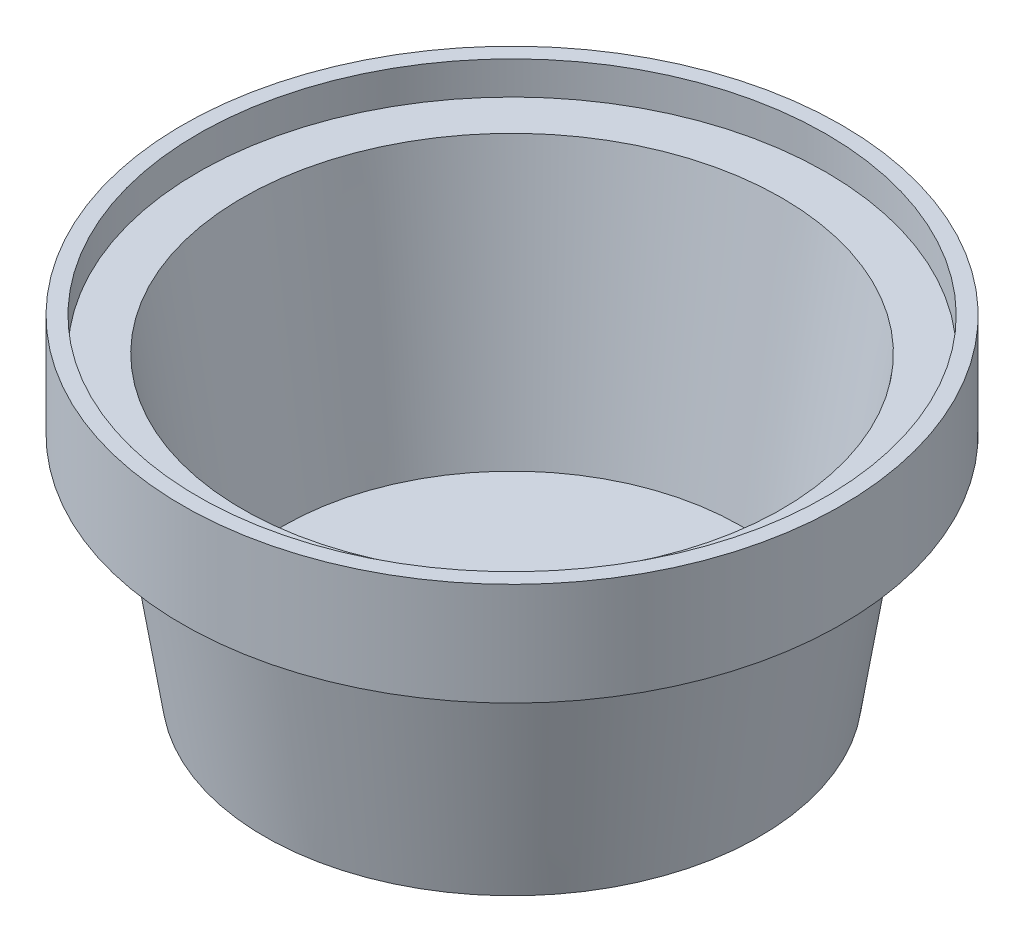
SolidWorks part; units mm, degrees
ref_plane "Front Plane" through (0, 0, 0) normal (0, 0, 1) x (1, 0, 0)
ref_plane "Top Plane" through (0, 0, 0) normal (0, 1, 0) x (1, 0, 0)
ref_plane "Right Plane" through (0, 0, 0) normal (1, 0, 0) x (0, 0, -1)
sketch "Sketch1" plane through (0, 0, 0) normal (0, 0, 1) x (1, 0, 0)
  line L0 (0, 0) -> (0, 40.9429) construction
  line L1 (37.465, 4.327) -> (44.1635, 47.507)
  line L2 (0, 4.327) -> (37.465, 4.327)
  line L3 (0, 4.327) -> (0, -0.753)
  line L4 (0, -0.753) -> (40.5325, -0.753)
  line L7 (47.625, 44.967) -> (40.5325, -0.753)
  line L9 (44.1635, 47.507) -> (51.435, 47.507)
  line L11 (47.625, 44.967) -> (51.435, 44.967)
  line L14 (53.975, 46.5741) -> (53.975, 36.077)
  line L15 (53.975, 36.077) -> (51.435, 36.077)
  line L16 (51.435, 44.967) -> (51.435, 36.077)
  line L18 (53.975, 46.5741) -> (53.975, 52.9241)
  line L19 (53.975, 52.9241) -> (51.435, 52.9241)
  line L20 (51.435, 47.507) -> (51.435, 52.9241)
  point P16 (34.4243, 47.507)
  point P17 (46.798, 49.1141)
  dimension "D1" = 5.08
  dimension "D2" = 3.81
  dimension "D3" = 2.54
  dimension "D4" = 2.54
  dimension "D5" = 6.35
  dimension "D6" = 43.18
  dimension "D7" = 8.89
  dimension "D8" = 37.465
  dimension "D9" = 3.81
  dimension "D10" = 47.625
revolve "Revolve1" add sketch "Sketch1" angle 360 about L0
sketch "Sketch2" plane through (0, 4.327, 0) normal (0, 1, 0) x (1, 0, 0)
  line L0 (0, 37.465) -> (0, -37.465) construction
  line L1 (12.8968, 0) -> (-12.8968, 0) construction
  circle A4 centre (0, 0) radius 37.465 construction
  circle A5 centre (-12.8968, 0) radius 8.001
  circle A6 centre (12.8968, 0) radius 8.001
  circle A7 centre (0, -29.9689) radius 2.2225
  point P9 (4.8959, 0)
  point P10 (-4.8959, 0)
  dimension "D1" = 16.002
  dimension "D3" = 4.445
  dimension "D2" = 9.7917
extrude "Cut-Extrude1" cut sketch "Sketch2" against normal through all
